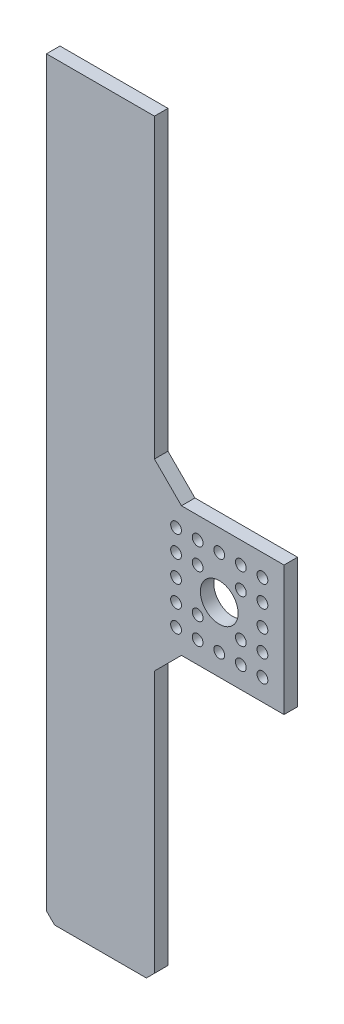
SolidWorks part; units mm, degrees
material "PMMA"
ref_plane "Front Plane" through (0, 0, 0) normal (0, 0, 1) x (1, 0, 0)
ref_plane "Top Plane" through (0, 0, 0) normal (0, 1, 0) x (1, 0, 0)
ref_plane "Right Plane" through (0, 0, 0) normal (1, 0, 0) x (0, 0, -1)
sketch "Sketch1" plane through (0, 0, 0) normal (0, 0, 1) x (1, 0, 0)
  line L0 (0, 0) -> (0, -278)
  line L1 (0, -278) -> (40, -278)
  line L2 (40, -278) -> (40, -168)
  line L3 (40, -168) -> (88, -168)
  line L4 (88, -168) -> (88, -120)
  line L5 (88, -120) -> (40, -120)
  line L6 (40, -120) -> (40, 0)
  line L7 (40, 0) -> (0, 0)
  line L8 (40, -120) -> (88, -168) construction
  line L9 (88, -120) -> (40, -168) construction
  line L10 (36.7207, -144) -> (92.7527, -144) construction
  line L11 (64, -114.6143) -> (64, -176.4365) construction
  circle A0 centre (64, -144) radius 7
  circle A1 centre (48, -128) radius 2
  circle A2 centre (56, -128) radius 2
  circle A3 centre (64, -128) radius 2
  circle A4 centre (72, -128) radius 2
  circle A5 centre (80, -128) radius 2
  circle A6 centre (56, -136) radius 2
  circle A8 centre (72, -136) radius 2
  circle A9 centre (80, -136) radius 2
  circle A13 centre (80, -144) radius 2
  circle A14 centre (56, -152) radius 2
  circle A16 centre (72, -152) radius 2
  circle A17 centre (80, -152) radius 2
  circle A18 centre (56, -160) radius 2
  circle A19 centre (64, -160) radius 2
  circle A20 centre (72, -160) radius 2
  circle A21 centre (80, -160) radius 2
  circle A22 centre (48, -136) radius 2
  circle A23 centre (48, -144) radius 2
  circle A24 centre (48, -152) radius 2
  circle A25 centre (48, -160) radius 2
  circle A26 centre (64, -136) radius 2 [skipped]
  circle A27 centre (56, -144) radius 2 [skipped]
  circle A28 centre (64, -144) radius 2 [skipped]
  circle A29 centre (72, -144) radius 2 [skipped]
  circle A30 centre (64, -152) radius 2 [skipped]
  dimension "D4" = 14
  dimension "D5" = 4
  dimension "D1" = 48
  dimension "D2" = 40
  dimension "D3" = 48
  dimension "D6" = 16
  dimension "D7" = 5
  dimension "D9" = 110
  dimension "D10" = 120
  dimension "D8" = 5
extrude "Boss-Extrude1" add sketch "Sketch1" along normal blind 5
chamfer "Chamfer2" distance 3 angle 45 2 edges at (0, -278, 2.5) (40, -278, 2.5)
chamfer "Chamfer3" distance 10 angle 45 2 edges at (40, -168, 2.5) (40, -120, 2.5)
